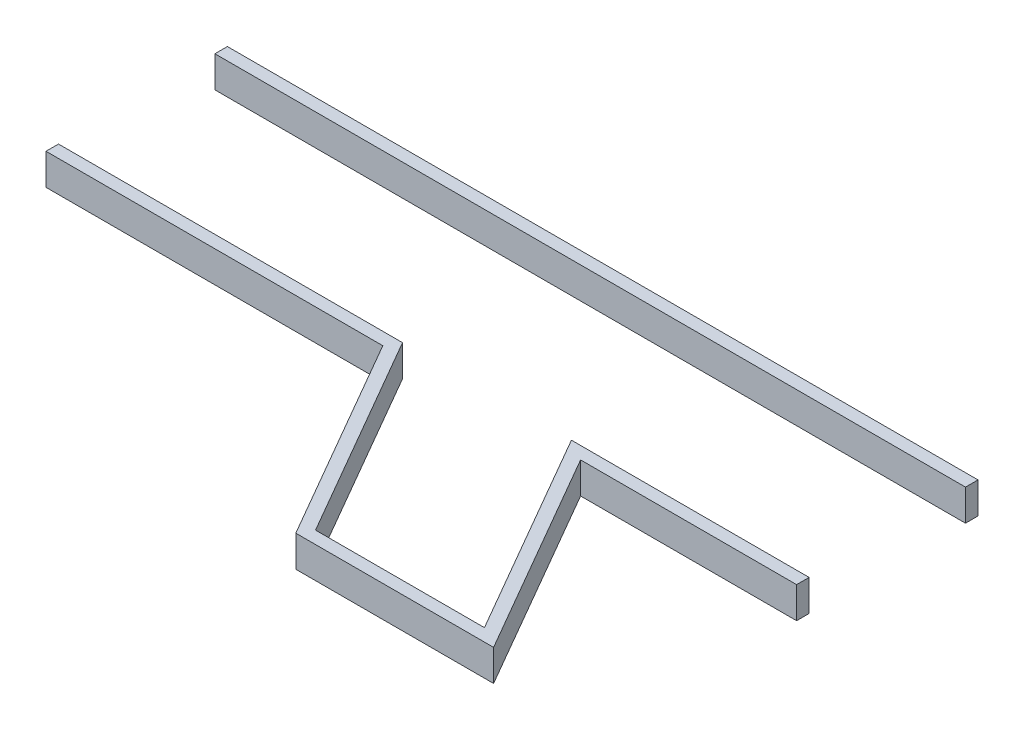
SolidWorks part; units mm, degrees
ref_plane "前视基准面" through (0, 0, 0) normal (0, 0, 1) x (1, 0, 0)
ref_plane "上视基准面" through (0, 0, 0) normal (0, 1, 0) x (1, 0, 0)
ref_plane "右视基准面" through (0, 0, 0) normal (1, 0, 0) x (0, 0, -1)
sketch "草图1" plane through (0, 0, 0) normal (0, 1, 0) x (1, 0, 0)
  line L0 (-600, 125) -> (600, 125)
  line L1 (-600, 145) -> (600, 145)
  line L2 (-600, 145) -> (-600, 125)
  line L3 (-600, -145) -> (-61.547, -145)
  line L4 (600, 145) -> (600, 125)
  line L5 (-600, 145) -> (600, -145) construction
  line L6 (-600, -145) -> (600, 145) construction
  line L8 (600, -125) -> (220, -125)
  line L9 (-50, -125) -> (140, -454.0897)
  line L10 (140, -454.0897) -> (410, -454.0897)
  line L11 (410, -454.0897) -> (220, -125)
  line L12 (220, -125) -> (243.094, -125)
  line L13 (254.641, -145) -> (444.641, -474.0897)
  line L14 (444.641, -474.0897) -> (128.453, -474.0897)
  line L15 (128.453, -474.0897) -> (-61.547, -145)
  line L16 (-600, -125) -> (-600, -145)
  line L17 (600, -125) -> (600, -145)
  line L18 (254.641, -145) -> (600, -145)
  line L19 (-50, -125) -> (-600, -125)
  line L20 (243.094, -125) -> (600, -125)
  point P0 (0, 0)
  point P14 (0, 0)
  dimension "D1" = 1200
  dimension "D2" = 20
  dimension "D3" = 250
  dimension "D4" = 20
  dimension "D5" = 270
  dimension "D6" = 20
  dimension "D7" = 20
  dimension "D8" = 20
  dimension "D9" = 550
  dimension "D10" = 60
  dimension "D11" = 380
extrude "凸台-拉伸1" add sketch "草图1" along normal blind 50 contours L9 L19 L16 L3 L15 L14 L13 L18 L17 L8 L11 L10 | L1 L4 L0 L2
